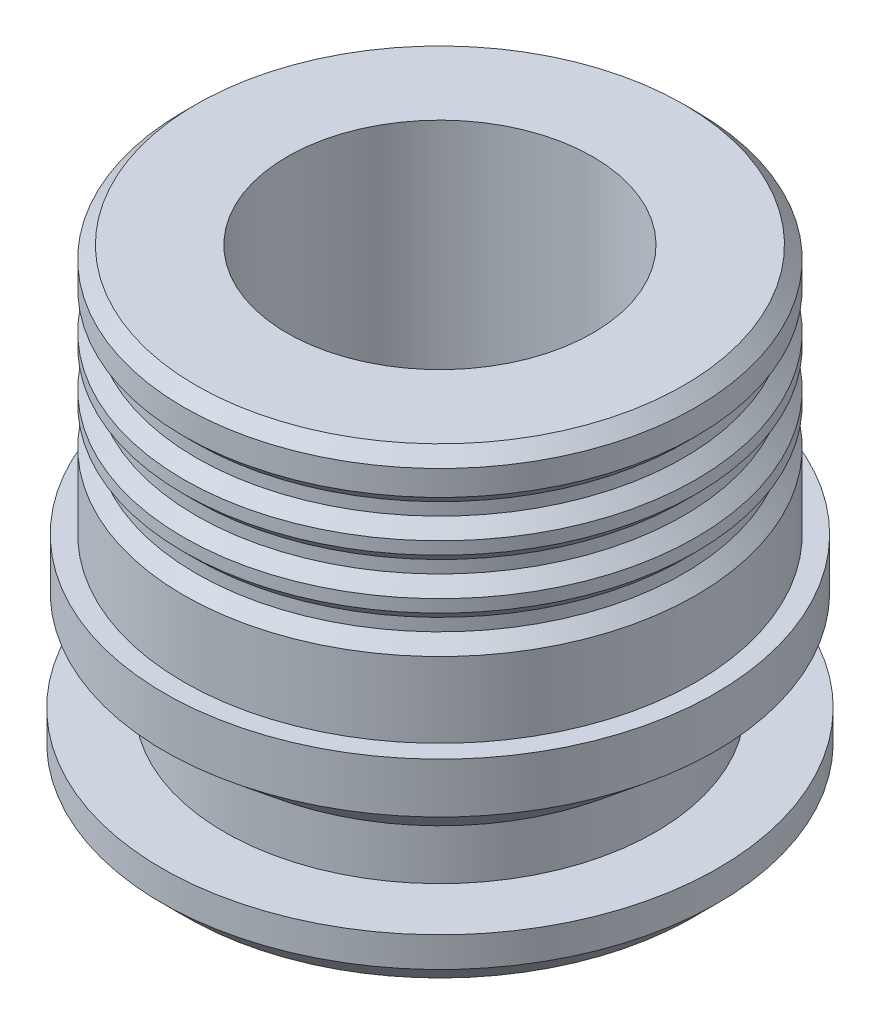
SolidWorks part; units mm, degrees
ref_plane "정면" through (0, 0, 0) normal (0, 0, 1) x (1, 0, 0)
ref_plane "윗면" through (0, 0, 0) normal (0, 1, 0) x (1, 0, 0)
ref_plane "우측면" through (0, 0, 0) normal (1, 0, 0) x (0, 0, -1)
sketch "스케치1" plane through (0, 0, 0) normal (1, 0, 0) x (0, 0, -1)
  line L0 (0, 0) -> (6.1, 0) construction
  line L1 (6.1, 0) -> (6.1, 18.2)
  line L2 (6.1, 18.2) -> (10.225, 18.2)
  line L3 (11, 8.2) -> (11, 6.2)
  line L4 (11, 6.2) -> (8.6, 4.2)
  line L5 (8.6, 4.2) -> (8.6, 2.2)
  line L6 (8.6, 2.2) -> (11.1, 2.2)
  line L7 (11.1, 2.2) -> (11.1, 0)
  line L8 (11.1, 0) -> (6.1, 0)
  line L9 (0, 0) -> (0, 18.2) construction
  line L10 (0, 18.2) -> (6.1, 18.2) construction
  line L11 (10.225, 18.2) -> (10.225, 16.7)
  line L12 (10.225, 8.2) -> (11, 8.2)
  line L16 (10.225, 11.2) -> (10.225, 8.2)
  line L17 (9.725, 12.2) -> (10.225, 12.7)
  line L18 (9.725, 11.7) -> (9.725, 12.2)
  line L19 (10.225, 11.2) -> (9.725, 11.7)
  line L20 (9.725, 14.2) -> (10.225, 14.7)
  line L21 (9.725, 13.7) -> (9.725, 14.2)
  line L22 (10.225, 13.2) -> (9.725, 13.7)
  line L23 (9.725, 16.2) -> (10.225, 16.7)
  line L24 (9.725, 15.7) -> (9.725, 16.2)
  line L25 (10.225, 15.2) -> (9.725, 15.7)
  line L27 (10.225, 13.2) -> (10.225, 12.7)
  line L28 (10.225, 15.2) -> (10.225, 14.7)
  dimension "D1" = 22.2
  dimension "D2" = 2.2
  dimension "D3" = 2
  dimension "D4" = 2
  dimension "D5" = 2
  dimension "D6" = 10
  dimension "D7" = 20.45
  dimension "D8" = 12.2
  dimension "D9" = 17.2
  dimension "D10" = 22
  dimension "D11" = 3
  dimension "D12" = 0.5
  dimension "D13" = 1.5
  dimension "D14" = 0.5
revolve "회전1" add sketch "스케치1" angle 360 about L9
chamfer "모따기1" distance 1 angle 45 1 edges at (0, 0, -11.1)
chamfer "모따기2" distance 0.5 angle 45 1 edges at (0, 18.2, -10.225)
chamfer "모따기3" distance 0.5 angle 45 1 edges at (0, 0, -6.1)
